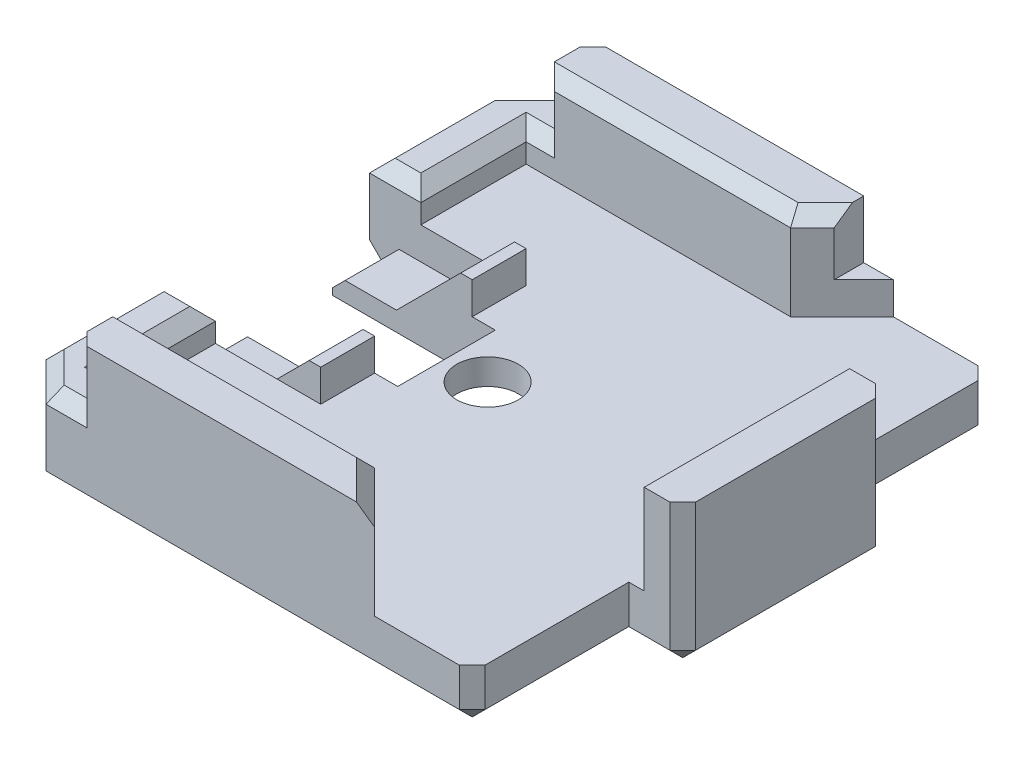
SolidWorks part; units mm, degrees
ref_plane "Front Plane" through (0, 0, 0) normal (0, 0, 1) x (1, 0, 0)
ref_plane "Top Plane" through (0, 0, 0) normal (0, 1, 0) x (1, 0, 0)
ref_plane "Right Plane" through (0, 0, 0) normal (1, 0, 0) x (0, 0, -1)
sketch "Sketch1" plane through (0, 0, 0) normal (0, 1, 0) x (1, 0, 0)
  line L0 (-503.2177, 0) -> (503.2177, 0) construction
  line L1 (-17.5, -7.5929) -> (-17.5, 7.5929) construction
  line L2 (20.5, -6.6675) -> (20.5, 6.6675) construction
  line L3 (9.5, -10.1) -> (9.5, -4)
  line L4 (-8.6, 10.1) -> (11.6, 10.1)
  line L5 (-8.6, 10.1) -> (-8.6, -10.1)
  line L6 (-8.6, -10.1) -> (11.6, -10.1)
  line L7 (11.6, 10.1) -> (11.6, -10.1)
  line L8 (9.5, -4) -> (11.6, -4)
  line L9 (9.5, 10.1) -> (9.5, 4)
  line L10 (9.5, 4) -> (11.6, 4)
  line L11 (-8.6, -4) -> (-7.95, -4)
  line L12 (-7.95, -4) -> (-7.95, -1.9)
  line L13 (-7.95, -1.9) -> (-1.6, -1.9)
  line L14 (-1.6, -1.9) -> (-1.6, 1.9)
  line L15 (-1.6, 1.9) -> (-7.95, 1.9)
  line L16 (-7.95, 1.9) -> (-7.95, 4)
  line L17 (-7.95, 4) -> (-8.6, 4)
  circle A0 centre (0, 0) radius 1.2
  point P5 (-2, 0)
  point P7 (-17.5, 0)
  point P10 (20.5, 0)
  point P14 (-8.6, 0)
  dimension "D16" = 2.4
  dimension "D3" = 8.9
  dimension "D4" = 15.5
  dimension "D5" = 20.2
  dimension "D6" = 2.1
  dimension "D7" = 6.1
  dimension "D8" = 6.1
  dimension "D9" = 2.1
  dimension "D10" = 2.1
  dimension "D11" = 0.65
  dimension "D13" = 6.1
  dimension "D14" = 6.1
  dimension "D17" = 38
  dimension "D2" = 8.6
  dimension "D15" = 8.9
  dimension "D12" = 7
extrude "Boss-Extrude1" add sketch "Sketch1" along normal blind 2 contours L17 L16 L15 L14 L13 L12 L11 L5 L6 L3 L8 L7 L10 L9 L4
sketch "Sketch2" plane through (0, 2, 0) normal (0, 1, 0) x (1, 0, 0)
  line L0 (-8.6, -4) -> (-7.95, -4)
  line L1 (-6.6, -4) -> (-6.6, -8.1)
  line L2 (-6.6, -8.1) -> (3.7, -8.1)
  line L3 (5.7, -8.1) -> (5.7, -10.1) construction
  line L4 (-8.6, -10.1) -> (9.5, -10.1) construction
  line L5 (5.7, -10.1) -> (-8.6, -10.1)
  line L6 (-8.6, -10.1) -> (-8.6, -4)
  line L7 (9.5, -10.1) -> (9.5, -4) construction
  line L8 (0, 0) -> (-11.463, 0) construction
  line L9 (-8.6, 10.1) -> (-8.6, 4)
  line L10 (5.7, 10.1) -> (-8.6, 10.1)
  line L12 (-6.6, 8.1) -> (3.7, 8.1)
  line L13 (-6.6, 4) -> (-6.6, 8.1)
  line L14 (-8.6, 4) -> (-7.95, 4)
  line L15 (9.5, -4) -> (11.6, -4) construction
  line L16 (11.6, 4) -> (9.6, 4)
  line L17 (11.6, 4) -> (11.6, -4)
  line L18 (11.6, -4) -> (9.6, -4)
  line L19 (9.6, 4) -> (9.6, -4)
  line L20 (-7.95, 4) -> (-6.6, 4) construction
  line L21 (-7.95, 1.9) -> (-2.5, 1.9)
  line L22 (-7.95, 1.9) -> (-7.95, 4)
  line L23 (-6.6, 4) -> (-2.5, 4)
  line L24 (-2.5, 1.9) -> (-2.5, 4)
  line L25 (-7.95, 4) -> (-6.6, 4) construction
  line L26 (-7.95, -4) -> (-6.6, -4) construction
  line L27 (-7.95, -1.9) -> (-2.5, -1.9)
  line L28 (-7.95, -1.9) -> (-7.95, -4)
  line L29 (-6.6, -4) -> (-2.5, -4)
  line L30 (-2.5, -1.9) -> (-2.5, -4)
  line L31 (-7.95, -4) -> (-6.6, -4) construction
  line L32 (5.7, -10.1) -> (3.7, -8.1)
  line L33 (3.7, -8.1) -> (5.7, -8.1) construction
  line L34 (5.7, 10.1) -> (3.7, 8.1)
  line L35 (3.7, 8.1) -> (-2.2, 8.1) construction
  line L36 (-8.6, 10.1) -> (9.5, 10.1) construction
  line L37 (9.5, 10.1) -> (9.5, 4) construction
  dimension "D1" = 2
  dimension "D2" = 2
  dimension "D3" = 3.8
  dimension "D4" = 2
  dimension "D5" = 6.1
  dimension "D6" = 6.1
  dimension "D7" = 45
  dimension "D8" = 45
  dimension "D9" = 3.8
extrude "Boss-Extrude2" add sketch "Sketch2" along normal blind 1.25
sketch "Sketch3" plane through (0, 3.25, 0) normal (0, 1, 0) x (1, 0, 0)
  line L0 (-8.6, -10.1) -> (5.7, -10.1) construction
  line L1 (11.6, 4) -> (9.6, 4)
  line L2 (11.6, 4) -> (11.6, -4)
  line L3 (11.6, -4) -> (9.6, -4)
  line L4 (9.6, 4) -> (9.6, -4)
  line L5 (3.7, -8.1) -> (-6, -8.1)
  line L6 (3.7, -8.1) -> (5.7, -10.1)
  line L7 (5.7, -10.1) -> (-6, -10.1)
  line L8 (-6, -8.1) -> (-6, -10.1)
  line L9 (5.7, 10.1) -> (-8.6, 10.1) construction
  line L10 (3.7, 8.1) -> (-6, 8.1)
  line L11 (3.7, 8.1) -> (4.55, 8.95)
  line L12 (4.55, 10.1) -> (-6, 10.1)
  line L13 (-6, 8.1) -> (-6, 10.1)
  line L14 (-8.6, 10.1) -> (-8.6, 4) construction
  line L15 (3.7, 8.1) -> (5.7, 10.1) construction
  line L16 (4.55, 10.1) -> (4.55, 8.95)
  line L17 (5.7, 10.1) -> (4.55, 10.1) construction
  line L18 (4.55, 8.95) -> (5.7, 10.1) construction
  dimension "D1" = 2.6
  dimension "D2" = 1.15
extrude "Boss-Extrude3" add sketch "Sketch3" along normal blind 2.25
sketch "Sketch4" plane through (0, 0, 0) normal (0, -1, 0) x (1, 0, 0)
  line L1 (-2.3094, 0) -> (-1.1547, -2)
  line L2 (-1.1547, -2) -> (1.1547, -2)
  line L3 (1.1547, -2) -> (2.3094, 0)
  line L4 (2.3094, 0) -> (1.1547, 2)
  line L5 (1.1547, 2) -> (-1.1547, 2)
  line L6 (-1.1547, 2) -> (-2.3094, 0)
  circle A0 centre (0, 0) radius 2 construction
  dimension "D1" = 4
extrude "Cut-Extrude1" cut sketch "Sketch4" against normal blind 1
sketch "Sketch5" plane through (0, 0, 1.9) normal (0, 0, -1) x (-1, 0, 0)
  line L0 (7.95, 0.75) -> (5.45, 0.75)
  line L1 (7.95, 3.25) -> (7.95, 0) construction
  line L2 (5.45, 0.75) -> (2.95, 3.25)
  line L3 (2.5, 3.25) -> (7.95, 3.25) construction
  line L4 (2.95, 3.25) -> (7.95, 3.25)
  line L5 (7.95, 3.25) -> (7.95, 0.75)
  line L6 (7.95, 0) -> (1.6, 0) construction
  dimension "D1" = 2.5
  dimension "D2" = 0.75
  dimension "D3" = 45
extrude "Cut-Extrude2" cut sketch "Sketch5" against normal up to surface (2.1 mm away) up to face at (-8.275, 1.625, 4)
sketch "Sketch6" plane through (0, 0, -1.9) normal (0, 0, 1) x (1, 0, 0)
  line L0 (-7.95, 3.25) -> (-7.95, 0.75)
  line L1 (-7.95, 3.25) -> (-7.95, 0) construction
  line L2 (-7.95, 0.75) -> (-5.45, 0.75)
  line L3 (-5.45, 0.75) -> (-2.95, 3.25)
  line L4 (-7.95, 3.25) -> (-2.5, 3.25) construction
  line L5 (-2.95, 3.25) -> (-7.95, 3.25)
  line L6 (-1.6, 0) -> (-7.95, 0) construction
  dimension "D1" = 0.75
  dimension "D2" = 45
  dimension "D3" = 2.5
extrude "Cut-Extrude3" cut sketch "Sketch6" against normal up to surface (2.1 mm away) up to face at (-8.275, 1.625, -4)
chamfer "Chamfer1" distance 1.5 angle 45 2 edges at (-8.6, 1.625, -10.1) (-8.6, 1.625, 10.1)
chamfer "Chamfer2" distance 0.5 angle 45 46 edges at (11.6, 2.75, -4) (11.6, 2.75, 4) (-8.6, 0, 6.3) (-7.85, 0, 9.35) (-8.6, 0, -6.3) (-7.85, 0, -9.35) (1.2, 0, -10.1) (9.5, 0, -7.05) (10.55, 0, -4) (1.2, 0, 10.1) (9.5, 0, 7.05) (10.55, 0, 4) (11.6, 0, 0) (-1.3774, 0, -1.6144) (0, 0, -2) (-1.3774, 0, 1.6144) (0, 0, 2) (1.7321, 0, 1) (1.7321, 0, -1) (-1.15, 5.5, -8.1) (-6, 4.375, -8.1) (-6.3, 3.25, -8.1) (-6.6, 3.25, -6.05) (-7.6, 3.25, -4) (-6.55, 3.25, -10.1) (-7.85, 3.25, -9.35) (-8.6, 3.25, -6.3) (-7.95, 0.75, 2.95) (-7.95, 0.75, -2.95) (9.6, 3.75, 4) (9.6, 3.75, -4) (9.6, 5.5, 0) (-1.15, 5.5, 8.1) (-6, 4.375, 8.1) (-6.3, 3.25, 8.1) (-6.6, 3.25, 6.05) (-7.6, 3.25, 4) (-6.55, 3.25, 10.1) (-7.85, 3.25, 9.35) (-8.6, 3.25, 6.3) (9.5, 1, -10.1) (9.5, 1, 10.1) (4.125, 5.5, -8.525) (4.7, 5.5, 9.1) (-6, 4.375, -10.1) (-6, 4.375, 10.1)
equation "\"d\" = 38mm"
equation "\"D17@Sketch1\"=\"d\""
